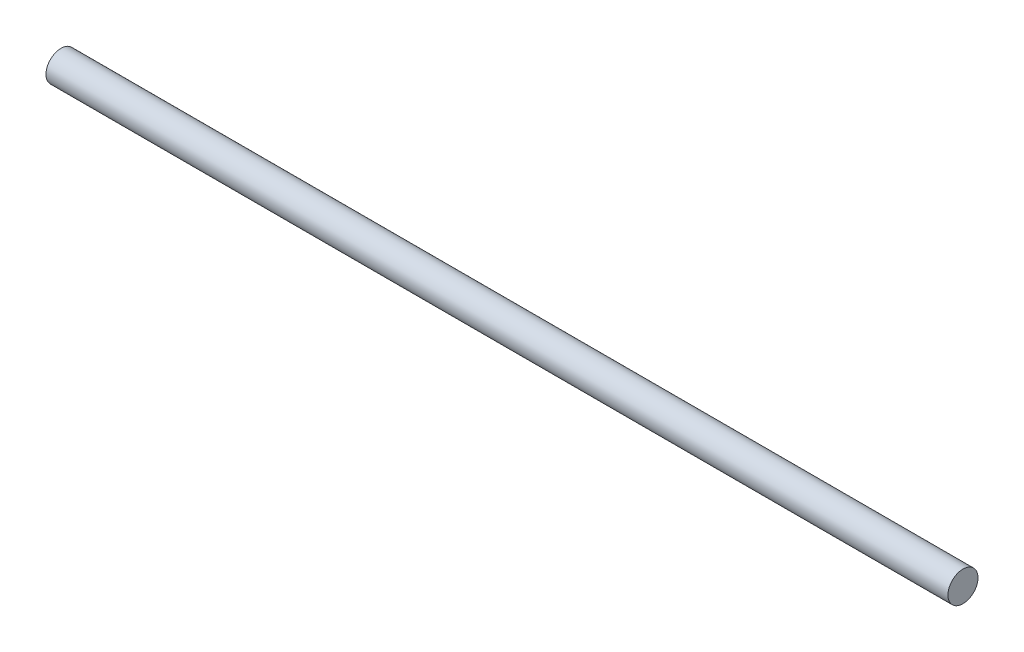
SolidWorks part; units mm, degrees
ref_plane "Front Plane" through (0, 0, 0) normal (1, 0, 0) x (0, 1, 0)
ref_plane "Top Plane" through (0, 0, 0) normal (0, 0, 1) x (0, 1, 0)
ref_plane "Right Plane" through (0, 0, 0) normal (0, 1, 0) x (-1, 0, 0)
sketch "Sketch1" plane through (0, 0, 0) normal (1, 0, 0) x (0, 1, 0)
  circle A0 centre (0, 0) radius 10
  dimension "D1" = 20
extrude "Boss-Extrude1" add sketch "Sketch1" along normal blind 600
cosmetic thread "Cosmetic Thread1" parameters "D2"=18.344
